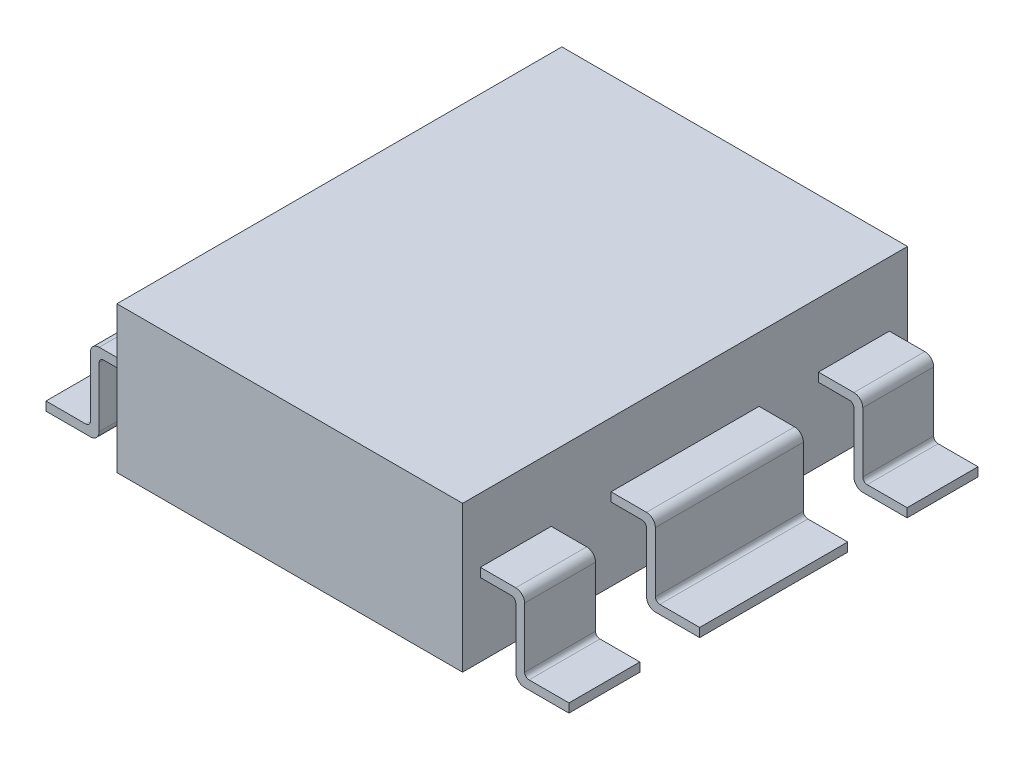
SolidWorks part; units mm, degrees
ref_plane "Front Plane" through (0, 0, 0) normal (0, 0, 1) x (1, 0, 0)
ref_plane "Top Plane" through (0, 0, 0) normal (0, 1, 0) x (1, 0, 0)
ref_plane "Right Plane" through (0, 0, 0) normal (1, 0, 0) x (0, 0, -1)
sketch "Sketch1" plane through (0, 0, 0) normal (0, 1, 0) x (1, 0, 0)
  line L1 (-1.95, -2.51) -> (1.95, -2.51)
  line L2 (-1.95, -2.51) -> (-1.95, 2.51)
  line L3 (-1.95, 2.51) -> (1.95, 2.51)
  line L4 (1.95, -2.51) -> (1.95, 2.51)
  line L5 (-1.95, -2.51) -> (1.95, 2.51) construction
  line L6 (-1.95, 2.51) -> (1.95, -2.51) construction
  point P0 (0, 0)
  dimension "D1" = 3.9
  dimension "D2" = 5.02
extrude "Boss-Extrude1" add sketch "Sketch1" along normal blind 1.65 contours L1 L4 L3 L2
sketch "Sketch2" plane through (0, 0, 2.51) normal (0, 0, 1) x (1, 0, 0)
  line L0 (2.95, 0) -> (2.45, 0)
  line L1 (2.35, 0.1) -> (2.35, 0.775)
  line L2 (2.3, 0.825) -> (1.95, 0.825)
  line L3 (1.95, 1.65) -> (1.95, 0) construction
  line L4 (1.25, 1.65) -> (1.25, 0) construction
  line L5 (-1.95, 1.65) -> (1.95, 1.65) construction
  line L6 (-1.95, 0) -> (1.95, 0) construction
  line L7 (1.25, 0.825) -> (1.95, 0.825) construction
  line L8 (2.95, 0.1) -> (2.5, 0.1)
  line L9 (2.45, 0.15) -> (2.45, 0.825)
  line L10 (2.35, 0.925) -> (1.95, 0.925)
  line L11 (2.95, 0.1) -> (2.95, 0)
  line L12 (1.95, 0.925) -> (1.95, 0.825)
  line L13 (2.35, 0) -> (2.35, 0.825) construction
  line L14 (2.35, 0.825) -> (1.95, 0.825) construction
  line L15 (2.95, 0.1) -> (2.45, 0.1) construction
  line L16 (2.45, 0.1) -> (2.45, 0.925) construction
  line L17 (2.95, 0) -> (2.35, 0) construction
  line L18 (2.45, 0.925) -> (1.95, 0.925) construction
  line L19 (0, 0) -> (0, 1.65) construction
  line L20 (-1.25, 0.825) -> (-1.95, 0.825) construction
  line L21 (-1.95, 0.925) -> (-1.95, 0.825)
  line L22 (-2.95, 0.1) -> (-2.95, 0)
  line L23 (-2.35, 0.925) -> (-1.95, 0.925)
  line L24 (-2.45, 0.15) -> (-2.45, 0.825)
  line L25 (-2.95, 0.1) -> (-2.5, 0.1)
  line L26 (-2.3, 0.825) -> (-1.95, 0.825)
  line L27 (-2.35, 0.1) -> (-2.35, 0.775)
  line L28 (-2.95, 0) -> (-2.45, 0)
  arc A0 (2.35, 0.775) -> (2.3, 0.825) centre (2.3, 0.775) ccw
  arc A1 (2.5, 0.1) -> (2.45, 0.15) centre (2.5, 0.15) cw
  arc A2 (2.45, 0) -> (2.35, 0.1) centre (2.45, 0.1) cw
  arc A3 (2.45, 0.825) -> (2.35, 0.925) centre (2.35, 0.825) ccw
  arc A4 (-2.45, 0.825) -> (-2.35, 0.925) centre (-2.35, 0.825) cw
  arc A5 (-2.45, 0) -> (-2.35, 0.1) centre (-2.45, 0.1) ccw
  arc A6 (-2.5, 0.1) -> (-2.45, 0.15) centre (-2.5, 0.15) ccw
  arc A7 (-2.35, 0.775) -> (-2.3, 0.825) centre (-2.3, 0.775) cw
  point P21 (2.35, 0.825)
  dimension "D4" = 0.05
  dimension "D5" = 0.05
  dimension "D6" = 0.1
  dimension "D1" = 0.1
  dimension "D2" = 0.4
  dimension "D3" = 0.1
extrude "Boss-Extrude2" add sketch "Sketch2" against normal up to surface (5.02 mm away) up to face at (0, 0.825, -2.51)
sketch "Sketch3" plane through (0, 1.65, 0) normal (0, 1, 0) x (1, 0, 0)
  line L0 (2.95, 2.51) -> (2.95, -2.51) construction
  line L1 (-2.95, 2.51) -> (-1.95, 2.51)
  line L2 (-2.95, 2.51) -> (-2.95, 2.305)
  line L3 (-2.95, 2.305) -> (-1.95, 2.305)
  line L4 (2.95, 2.51) -> (2.95, 2.305)
  line L5 (-2.95, 2.51) -> (-2.95, -2.51) construction
  line L6 (-2.95, 1.505) -> (-1.95, 1.505)
  line L7 (-2.95, 1.505) -> (-2.95, 0.835)
  line L8 (-2.95, 0.835) -> (-1.95, 0.835)
  line L9 (2.95, 1.505) -> (2.95, 0.835)
  line L11 (-2.95, -0.835) -> (-1.95, -0.835)
  line L12 (-2.95, -0.835) -> (-2.95, -1.51)
  line L13 (-2.95, -1.51) -> (-1.95, -1.51)
  line L14 (2.95, -0.835) -> (2.95, -1.51)
  line L15 (2.95, -2.51) -> (1.95, -2.51)
  line L16 (2.95, -2.51) -> (2.95, -2.31)
  line L17 (2.95, -2.31) -> (1.95, -2.31)
  line L18 (-2.95, -2.51) -> (-2.95, -2.31)
  line L21 (-1.95, -2.51) -> (-1.95, -2.31)
  line L22 (-1.95, -1.51) -> (-1.95, -0.835)
  line L23 (-1.95, 2.51) -> (-1.95, -2.51) construction
  line L24 (-1.95, 0.835) -> (-1.95, 1.505)
  line L25 (-1.95, 2.305) -> (-1.95, 2.51)
  line L26 (1.95, -2.51) -> (1.95, -2.31)
  line L27 (1.95, 2.51) -> (1.95, -2.51) construction
  line L28 (1.95, -1.51) -> (1.95, -0.835)
  line L29 (1.95, -2.51) -> (1.95, 2.51) construction
  line L30 (1.95, 0.835) -> (1.95, 1.505)
  line L31 (1.95, 2.305) -> (1.95, 2.51)
  line L32 (1.95, 2.51) -> (2.95, 2.51)
  line L33 (1.95, 2.305) -> (2.95, 2.305)
  line L34 (1.95, 1.505) -> (2.95, 1.505)
  line L35 (1.95, 0.835) -> (2.95, 0.835)
  line L36 (1.95, -0.835) -> (2.95, -0.835)
  line L37 (1.95, -1.51) -> (2.95, -1.51)
  line L38 (-1.95, -2.31) -> (-2.95, -2.31)
  line L39 (-1.95, -2.51) -> (-2.95, -2.51)
extrude "Cut-Extrude1" cut sketch "Sketch3" against normal through all
